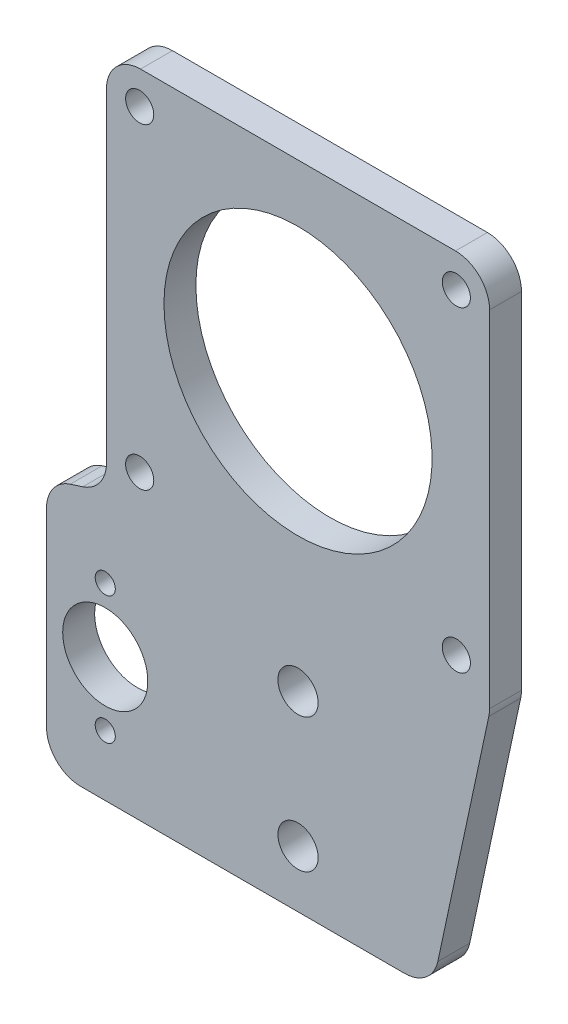
SolidWorks part; units mm, degrees
ref_plane "Front Plane" through (0, 0, 0) normal (0, 0, 1) x (1, 0, 0)
ref_plane "Top Plane" through (0, 0, 0) normal (0, 1, 0) x (1, 0, 0)
ref_plane "Right Plane" through (0, 0, 0) normal (1, 0, 0) x (0, 0, -1)
sketch "Sketch1" plane through (0, 0, 0) normal (0, 0, 1) x (1, 0, 0)
  line L0 (0, 0) -> (-8.945, -2.86)
  line L1 (-8.945, -2.86) -> (-8.945, -40)
  line L2 (57.15, 0) -> (57.15, 57.15)
  line L3 (57.15, 57.15) -> (0, 57.15)
  line L4 (0, 0) -> (0, 57.15)
  line L9 (57.15, 0) -> (48.575, -40)
  line L13 (8.575, -40) -> (-8.945, -40)
  line L20 (48.575, -40) -> (8.575, -40)
  circle A0 centre (-0.185, -21.43) radius 6.35
  circle A1 centre (4.953, 52.2331) radius 2.75
  circle A2 centre (4.953, 4.9891) radius 2.75
  circle A3 centre (52.197, 4.9891) radius 2.75
  circle A4 centre (52.197, 52.197) radius 2.75
  circle A5 centre (28.575, -31.5) radius 3
  circle A6 centre (28.575, -11.5) radius 3
  circle A7 centre (28.575, 28.575) radius 5
  circle A8 centre (28.575, 28.575) radius 20
  point P0 (28.575, 28.575)
  point P5 (-0.185, -30.96)
  point P10 (-0.185, -11.9)
  dimension "D1" = 57.15
  dimension "D2" = 12.7
  dimension "D3" = 5.5
  dimension "D5" = 6
  dimension "D9" = 8.575
  dimension "D6" = 8.5
  dimension "D4" = 28.76
  dimension "D7" = 20
  dimension "D8" = 0
  dimension "D10" = 18.57
  dimension "D11" = 18.57
  dimension "D12" = 17.52
  dimension "D13" = 40
  dimension "D14" = 9.53
  dimension "D15" = 9.53
  dimension "D16" = 20
extrude "Boss-Extrude1" add sketch "Sketch1" along normal blind 4.7625
fillet "Fillet1" radius 5.08 7 edges at (57.15, 57.15, 2.3813) (0, 57.15, 2.3813) (57.15, 0, 2.3813) (48.575, -40, 2.3813) (0, 0, 2.3813) (-8.945, -40, 2.3813) (-8.945, -2.86, 2.3813)
hole_wizard "M5 Tapped Hole1" positions "Sketch3" profile "Sketch2" tap size "M5" standard "ISO"
sketch "Sketch3" plane through (0, 0, 4.7625) normal (0, 0, 1) x (1, 0, 0)
  point P0 (4.953, 52.2331)
  point P3 (52.197, 52.197)
  point P6 (52.197, 4.9891)
  point P9 (4.953, 4.9891)
sketch "Sketch2" plane through (4.953, 52.2331, 4.7625) normal (1, 0, 0) x (0, -1, 0)
  line L0 (0, 0) -> (0, 15.2618)
  line L1 (0, 15.2618) -> (2.1, 14)
  line L2 (2.1, 14) -> (2.1, 0)
  line L5 (2.1, 0) -> (0, 0)
  line L10 (0, 15.2618) -> (-2.1, 14) construction
  line L11 (0, -6.35) -> (0, 107.95) construction
  dimension "Tap Drill Dia." = 4.2
  dimension "Tap Drill Depth" = 14
  dimension "Drill Angle" = 118
cosmetic thread "Hole Thread1" parameters "D1"=4.7625, "D2"=5
cosmetic thread "Hole Thread2" parameters "D1"=4.7625, "D2"=5
cosmetic thread "Hole Thread3" parameters "D1"=4.7625, "D2"=5
cosmetic thread "Hole Thread4" parameters "D1"=4.7625, "D2"=5
hole_wizard "Ø3.0 (3) Diameter Hole1" positions "Sketch5" profile "Sketch4" hole size "Ø3.0" standard "ANSI Metric"
sketch "Sketch5" plane through (0, 0, 0) normal (0, 0, -1) x (-1, 0, 0)
  point P0 (0.185, -30.96)
  point P3 (0.185, -11.9)
sketch "Sketch4" plane through (-0.185, -30.96, 0) normal (1, 0, 0) x (0, 1, 0)
  line L0 (0, 0) -> (0, 26.3013)
  line L1 (0, 26.3013) -> (1.5, 25.4)
  line L2 (1.5, 25.4) -> (1.5, 0)
  line L5 (1.5, 0) -> (0, 0)
  line L10 (0, 26.3013) -> (-1.5, 25.4) construction
  line L11 (0, -6.35) -> (0, 107.95) construction
  dimension "Hole Dia." = 3
  dimension "Hole Depth" = 25.4
  dimension "Drill Angle" = 118
